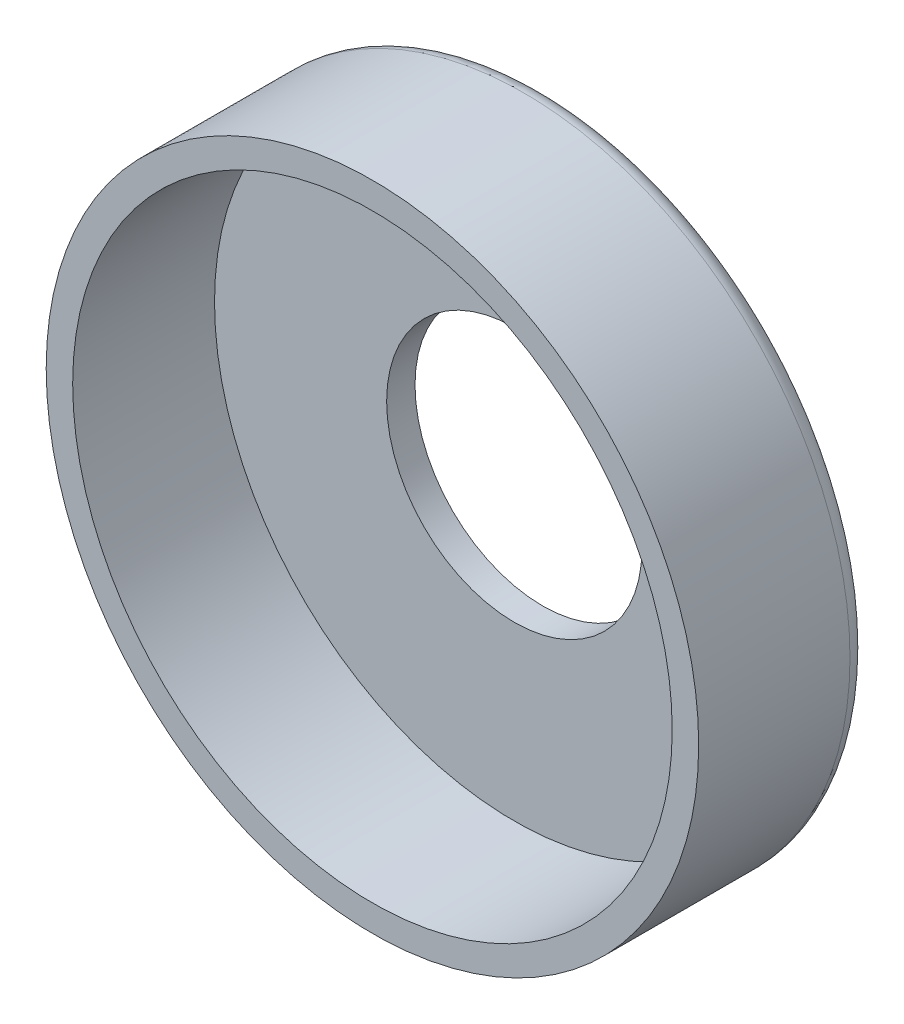
SolidWorks part; units mm, degrees
ref_plane "Front" through (0, 0, 0) normal (0, 0, 1) x (1, 0, 0)
ref_plane "Top" through (0, 0, 0) normal (0, 1, 0) x (1, 0, 0)
ref_plane "Right" through (0, 0, 0) normal (1, 0, 0) x (0, 0, -1)
sketch "Esquisse1" plane through (0, 0, 0) normal (0, 0, 1) x (1, 0, 0)
  circle A0 centre (0, 0) radius 34.5
  dimension "D1" = 69
extrude "Boss.-Extru.1" add sketch "Esquisse1" along normal blind 3
sketch "Esquisse2" plane through (0, 0, 3) normal (0, 0, 1) x (1, 0, 0)
  circle A0 centre (0, 0) radius 34.5
  circle A1 centre (0, 0) radius 31.7
  dimension "D1" = 69
  dimension "D2" = 2.8
extrude "Boss.-Extru.2" add sketch "Esquisse2" along normal blind 15
sketch "Esquisse3" plane through (0, 0, 0) normal (0, 0, -1) x (-1, 0, 0)
  circle A0 centre (0, 0) radius 13.5
  dimension "D1" = 27
extrude "Enlèv. mat.-Extru.1" cut sketch "Esquisse3" against normal through all both and the other way through all
fillet "Congé1" radius 2 1 edges at (34.5, 0, 0)
